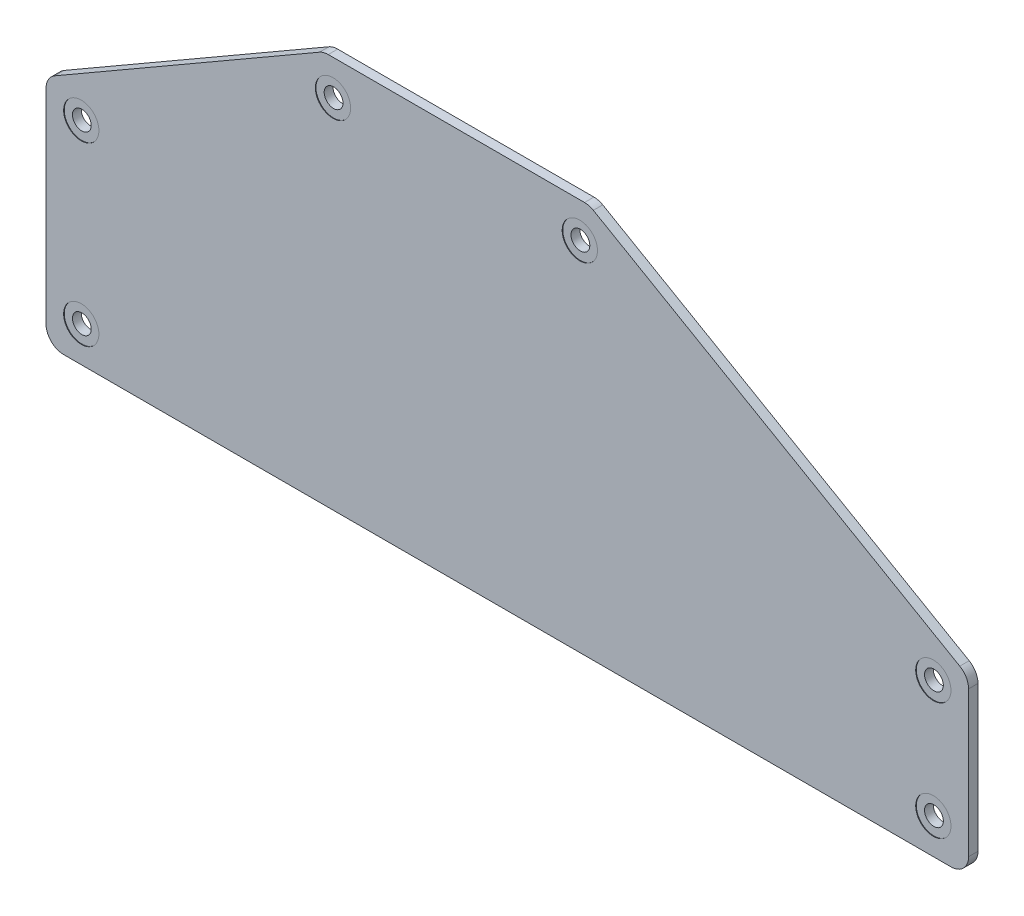
SolidWorks part; units mm, degrees
ref_plane "Front Plane" through (0, 0, 0) normal (0, 0, 1) x (1, 0, 0)
ref_plane "Top Plane" through (0, 0, 0) normal (0, 1, 0) x (1, 0, 0)
ref_plane "Right Plane" through (0, 0, 0) normal (1, 0, 0) x (0, 0, -1)
sketch "Sketch1" plane through (0, 0, 0) normal (0, 0, 1) x (1, 0, 0)
  line L0 (0, 0) -> (157, 0)
  line L1 (69.8397, 85.5596) -> (-55.1603, 13.3908) construction
  line L2 (-55.1603, 13.3908) -> (-55.1603, -130.9468) construction
  line L3 (-55.1603, -130.9468) -> (69.8397, -203.1155) construction
  line L4 (69.8397, -203.1155) -> (194.8397, -130.9468) construction
  line L5 (194.8397, -130.9468) -> (194.8397, 13.3908) construction
  line L6 (194.8397, 13.3908) -> (69.8397, 85.5596) construction
  line L7 (157, 0) -> (157, 29.4641)
  line L8 (157, 29.4641) -> (92.4474, 66.7335)
  line L9 (92.4474, 66.7335) -> (47.2321, 66.7335)
  line L10 (47.2321, 66.7335) -> (0, 39.4641)
  line L11 (0, 39.4641) -> (0, 0)
  line L12 (6, 36) -> (6, 6) construction
  line L13 (151, 26) -> (151, 6) construction
  line L14 (48.8397, 60.7335) -> (90.8397, 60.7335) construction
  line L15 (6, 6) -> (151, 6) construction
  line L16 (6, 6) -> (6, 0) construction
  line L17 (6, 6) -> (0, 6) construction
  line L18 (151, 6) -> (157, 6) construction
  line L19 (6, 36) -> (3, 41.1962) construction
  line L20 (151, 26) -> (154, 31.1962) construction
  line L21 (48.8397, 60.7335) -> (48.8397, 66.7335) construction
  line L22 (48.8397, 60.7335) -> (45.8397, 65.9297) construction
  line L23 (90.8397, 60.7335) -> (93.8397, 65.9297) construction
  line L24 (6, 36) -> (48.8397, 60.7335) construction
  line L25 (151, 26) -> (90.8397, 60.7335) construction
  circle A0 centre (69.8397, -58.778) radius 125 construction
  circle A1 centre (6, 36) radius 1.6
  circle A2 centre (6, 6) radius 1.6
  circle A3 centre (151, 6) radius 1.6
  circle A4 centre (151, 26) radius 1.6
  circle A5 centre (90.8397, 60.7335) radius 1.6
  circle A6 centre (48.8397, 60.7335) radius 1.6
  dimension "D9" = 3.2
  dimension "D1" = 250
  dimension "D2" = 5
  dimension "D3" = 5
  dimension "D4" = 42
  dimension "D5" = 145
  dimension "D6" = 20
  dimension "D7" = 6
  dimension "D8" = 30
extrude "Boss-Extrude1" add sketch "Sketch1" along normal blind 1.6
fillet "Fillet1" radius 3 6 edges at (0, 39.4641, 0.8) (47.2321, 66.7335, 0.8) (92.4474, 66.7335, 0.8) (157, 29.4641, 0.8) (157, 0, 0.8) (0, 0, 0.8)
sketch "Sketch2" plane through (0, 0, 1.6) normal (0, 0, 1) x (1, 0, 0)
  line L6 (46.5359, 66.3316) -> (1.5, 40.3301)
  line L7 (0, 37.7321) -> (0, 3)
  line L8 (3, 0) -> (154, 0)
  line L9 (157, 3) -> (157, 27.7321)
  line L10 (155.5, 30.3301) -> (93.1436, 66.3316)
  line L11 (91.6436, 66.7335) -> (48.0359, 66.7335)
  line L12 (46.5359, 66.3316) -> (1.5, 40.3301) construction
  line L13 (0, 37.7321) -> (0, 3) construction
  line L14 (3, 0) -> (154, 0) construction
  line L15 (157, 3) -> (157, 27.7321) construction
  line L16 (155.5, 30.3301) -> (93.1436, 66.3316) construction
  line L17 (91.6436, 66.7335) -> (48.0359, 66.7335) construction
  circle A0 centre (6, 6) radius 3
  circle A1 centre (6, 36) radius 3
  circle A2 centre (48.8397, 60.7335) radius 3
  circle A3 centre (90.8397, 60.7335) radius 3
  circle A4 centre (151, 26) radius 3
  circle A5 centre (151, 6) radius 3
  arc A6 (1.5, 40.3301) -> (0, 37.7321) centre (3, 37.7321) ccw
  arc A7 (0, 3) -> (3, 0) centre (3, 3) ccw
  arc A8 (154, 0) -> (157, 3) centre (154, 3) ccw
  arc A9 (157, 27.7321) -> (155.5, 30.3301) centre (154, 27.7321) ccw
  arc A10 (93.1436, 66.3316) -> (91.6436, 66.7335) centre (91.6436, 63.7335) ccw
  arc A11 (48.0359, 66.7335) -> (46.5359, 66.3316) centre (48.0359, 63.7335) ccw
  arc A12 (1.5, 40.3301) -> (0, 37.7321) centre (3, 37.7321) ccw construction
  arc A13 (0, 3) -> (3, 0) centre (3, 3) ccw construction
  arc A14 (154, 0) -> (157, 3) centre (154, 3) ccw construction
  arc A15 (157, 27.7321) -> (155.5, 30.3301) centre (154, 27.7321) ccw construction
  arc A16 (93.1436, 66.3316) -> (91.6436, 66.7335) centre (91.6436, 63.7335) ccw construction
  arc A17 (48.0359, 66.7335) -> (46.5359, 66.3316) centre (48.0359, 63.7335) ccw construction
  dimension "D2" = 6
  dimension "D1" = 0
extrude "Cut-Extrude1" cut sketch "Sketch2" against normal blind 0.1
